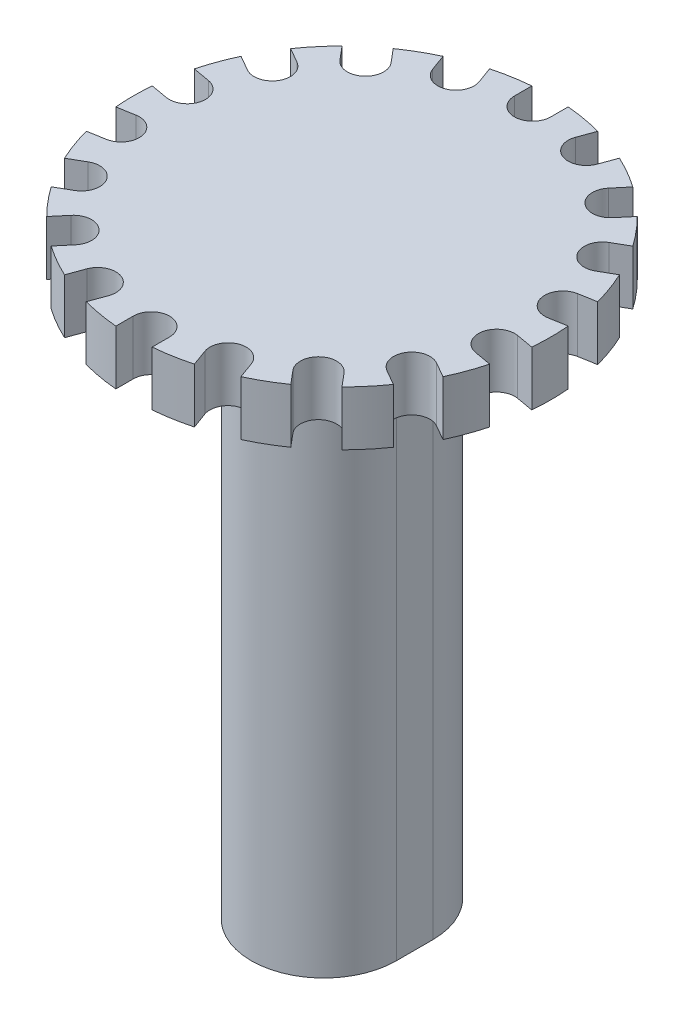
SolidWorks part; units mm, degrees
ref_plane "Front Plane" through (0, 0, 0) normal (0, 0, 1) x (1, 0, 0)
ref_plane "Top Plane" through (0, 0, 0) normal (0, 1, 0) x (1, 0, 0)
ref_plane "Right Plane" through (0, 0, 0) normal (1, 0, 0) x (0, 0, -1)
sketch "Sketch1" plane through (0, 0, 0) normal (0, 1, 0) x (1, 0, 0)
  line L0 (0, -0.8) -> (0, 0.8) construction
  line L1 (-2, -0.8) -> (-2, 0.8)
  line L2 (2, -0.8) -> (2, 0.8)
  line L3 (0, -1) -> (0, 1) construction
  line L4 (-4, -1) -> (-4, 1)
  line L5 (4, -1) -> (4, 1)
  arc A0 (-2, -0.8) -> (2, -0.8) centre (0, -0.8) ccw
  arc A1 (2, 0.8) -> (-2, 0.8) centre (0, 0.8) ccw
  arc A2 (-4, -1) -> (4, -1) centre (0, -1) ccw
  arc A3 (4, 1) -> (-4, 1) centre (0, 1) ccw
  point P2 (0, 0)
  point P9 (0, 0)
  dimension "D3" = 1.6
  dimension "D4" = 2
  dimension "D1" = 4
  dimension "D2" = 8
extrude "Boss-Extrude1" add sketch "Sketch1" along normal blind 30
sketch "Sketch2" plane through (0, 30, 0) normal (0, 1, 0) x (1, 0, 0)
  circle A0 centre (0, 0) radius 11.5
  dimension "D1" = 23
extrude "Boss-Extrude2" add sketch "Sketch2" along normal blind 3
sketch "Sketch3" plane through (0, 33, 0) normal (0, 1, 0) x (1, 0, 0)
  line L0 (0, 10.5) -> (0, 17.5) construction
  line L1 (-1, 10.5) -> (-1, 17.5)
  line L2 (1, 10.5) -> (1, 17.5)
  line L3 (3.5912, 9.8668) -> (5.9854, 16.4446) construction
  line L4 (2.6515, 10.2088) -> (5.0457, 16.7866)
  line L5 (4.5309, 9.5248) -> (6.925, 16.1026)
  line L6 (6.7493, 8.0435) -> (11.2488, 13.4058) construction
  line L7 (5.9832, 8.6863) -> (10.4827, 14.0486)
  line L8 (7.5153, 7.4007) -> (12.0148, 12.763)
  line L9 (9.0933, 5.25) -> (15.1554, 8.75) construction
  line L10 (8.5933, 6.116) -> (14.6554, 9.616)
  line L11 (9.5933, 4.384) -> (15.6554, 7.884)
  line L12 (10.3405, 1.8233) -> (17.2341, 3.0388) construction
  line L13 (10.1668, 2.8081) -> (17.0605, 4.0237)
  line L14 (10.5141, 0.8385) -> (17.4078, 2.054)
  line L15 (10.3405, -1.8233) -> (17.2341, -3.0388) construction
  line L16 (10.5141, -0.8385) -> (17.4078, -2.054)
  line L17 (10.1668, -2.8081) -> (17.0605, -4.0237)
  line L18 (9.0933, -5.25) -> (15.1554, -8.75) construction
  line L19 (9.5933, -4.384) -> (15.6554, -7.884)
  line L20 (8.5933, -6.116) -> (14.6554, -9.616)
  line L21 (6.7493, -8.0435) -> (11.2488, -13.4058) construction
  line L22 (7.5153, -7.4007) -> (12.0148, -12.763)
  line L23 (5.9832, -8.6863) -> (10.4827, -14.0486)
  line L24 (3.5912, -9.8668) -> (5.9854, -16.4446) construction
  line L25 (4.5309, -9.5248) -> (6.925, -16.1026)
  line L26 (2.6515, -10.2088) -> (5.0457, -16.7866)
  line L27 (0, -10.5) -> (0, -17.5) construction
  line L28 (1, -10.5) -> (1, -17.5)
  line L29 (-1, -10.5) -> (-1, -17.5)
  line L30 (-3.5912, -9.8668) -> (-5.9854, -16.4446) construction
  line L31 (-2.6515, -10.2088) -> (-5.0457, -16.7866)
  line L32 (-4.5309, -9.5248) -> (-6.925, -16.1026)
  line L33 (-6.7493, -8.0435) -> (-11.2488, -13.4058) construction
  line L34 (-5.9832, -8.6863) -> (-10.4827, -14.0486)
  line L35 (-7.5153, -7.4007) -> (-12.0148, -12.763)
  line L36 (-9.0933, -5.25) -> (-15.1554, -8.75) construction
  line L37 (-8.5933, -6.116) -> (-14.6554, -9.616)
  line L38 (-9.5933, -4.384) -> (-15.6554, -7.884)
  line L39 (-10.3405, -1.8233) -> (-17.2341, -3.0388) construction
  line L40 (-10.1668, -2.8081) -> (-17.0605, -4.0237)
  line L41 (-10.5141, -0.8385) -> (-17.4078, -2.054)
  line L42 (-10.3405, 1.8233) -> (-17.2341, 3.0388) construction
  line L43 (-10.5141, 0.8385) -> (-17.4078, 2.054)
  line L44 (-10.1668, 2.8081) -> (-17.0605, 4.0237)
  line L45 (-9.0933, 5.25) -> (-15.1554, 8.75) construction
  line L46 (-9.5933, 4.384) -> (-15.6554, 7.884)
  line L47 (-8.5933, 6.116) -> (-14.6554, 9.616)
  line L48 (-6.7493, 8.0435) -> (-11.2488, 13.4058) construction
  line L49 (-7.5153, 7.4007) -> (-12.0148, 12.763)
  line L50 (-5.9832, 8.6863) -> (-10.4827, 14.0486)
  line L51 (-3.5912, 9.8668) -> (-5.9854, 16.4446) construction
  line L52 (-4.5309, 9.5248) -> (-6.925, 16.1026)
  line L53 (-2.6515, 10.2088) -> (-5.0457, 16.7866)
  arc A0 (2.6515, 10.2088) -> (4.5309, 9.5248) centre (3.5912, 9.8668) ccw
  arc A1 (-1, 10.5) -> (1, 10.5) centre (0, 10.5) ccw
  arc A2 (1, 17.5) -> (-1, 17.5) centre (0, 17.5) ccw
  arc A3 (6.925, 16.1026) -> (5.0457, 16.7866) centre (5.9854, 16.4446) ccw
  arc A4 (5.9832, 8.6863) -> (7.5153, 7.4007) centre (6.7493, 8.0435) ccw
  arc A5 (12.0148, 12.763) -> (10.4827, 14.0486) centre (11.2488, 13.4058) ccw
  arc A6 (8.5933, 6.116) -> (9.5933, 4.384) centre (9.0933, 5.25) ccw
  arc A7 (15.6554, 7.884) -> (14.6554, 9.616) centre (15.1554, 8.75) ccw
  arc A8 (10.1668, 2.8081) -> (10.5141, 0.8385) centre (10.3405, 1.8233) ccw
  arc A9 (17.4078, 2.054) -> (17.0605, 4.0237) centre (17.2341, 3.0388) ccw
  arc A10 (10.5141, -0.8385) -> (10.1668, -2.8081) centre (10.3405, -1.8233) ccw
  arc A11 (17.0605, -4.0237) -> (17.4078, -2.054) centre (17.2341, -3.0388) ccw
  arc A12 (9.5933, -4.384) -> (8.5933, -6.116) centre (9.0933, -5.25) ccw
  arc A13 (14.6554, -9.616) -> (15.6554, -7.884) centre (15.1554, -8.75) ccw
  arc A14 (7.5153, -7.4007) -> (5.9832, -8.6863) centre (6.7493, -8.0435) ccw
  arc A15 (10.4827, -14.0486) -> (12.0148, -12.763) centre (11.2488, -13.4058) ccw
  arc A16 (4.5309, -9.5248) -> (2.6515, -10.2088) centre (3.5912, -9.8668) ccw
  arc A17 (5.0457, -16.7866) -> (6.925, -16.1026) centre (5.9854, -16.4446) ccw
  arc A18 (1, -10.5) -> (-1, -10.5) centre (0, -10.5) ccw
  arc A19 (-1, -17.5) -> (1, -17.5) centre (0, -17.5) ccw
  arc A20 (-2.6515, -10.2088) -> (-4.5309, -9.5248) centre (-3.5912, -9.8668) ccw
  arc A21 (-6.925, -16.1026) -> (-5.0457, -16.7866) centre (-5.9854, -16.4446) ccw
  arc A22 (-5.9832, -8.6863) -> (-7.5153, -7.4007) centre (-6.7493, -8.0435) ccw
  arc A23 (-12.0148, -12.763) -> (-10.4827, -14.0486) centre (-11.2488, -13.4058) ccw
  arc A24 (-8.5933, -6.116) -> (-9.5933, -4.384) centre (-9.0933, -5.25) ccw
  arc A25 (-15.6554, -7.884) -> (-14.6554, -9.616) centre (-15.1554, -8.75) ccw
  arc A26 (-10.1668, -2.8081) -> (-10.5141, -0.8385) centre (-10.3405, -1.8233) ccw
  arc A27 (-17.4078, -2.054) -> (-17.0605, -4.0237) centre (-17.2341, -3.0388) ccw
  arc A28 (-10.5141, 0.8385) -> (-10.1668, 2.8081) centre (-10.3405, 1.8233) ccw
  arc A29 (-17.0605, 4.0237) -> (-17.4078, 2.054) centre (-17.2341, 3.0388) ccw
  arc A30 (-9.5933, 4.384) -> (-8.5933, 6.116) centre (-9.0933, 5.25) ccw
  arc A31 (-14.6554, 9.616) -> (-15.6554, 7.884) centre (-15.1554, 8.75) ccw
  arc A32 (-7.5153, 7.4007) -> (-5.9832, 8.6863) centre (-6.7493, 8.0435) ccw
  arc A33 (-10.4827, 14.0486) -> (-12.0148, 12.763) centre (-11.2488, 13.4058) ccw
  arc A34 (-4.5309, 9.5248) -> (-2.6515, 10.2088) centre (-3.5912, 9.8668) ccw
  arc A35 (-5.0457, 16.7866) -> (-6.925, 16.1026) centre (-5.9854, 16.4446) ccw
  point P2 (0, 14)
  point P11 (4.7883, 13.1557)
  point P18 (8.999, 10.7246)
  point P25 (12.1244, 7)
  point P32 (13.7873, 2.4311)
  point P39 (13.7873, -2.4311)
  point P46 (12.1244, -7)
  point P53 (8.999, -10.7246)
  point P60 (4.7883, -13.1557)
  point P67 (0, -14)
  point P74 (-4.7883, -13.1557)
  point P81 (-8.999, -10.7246)
  point P88 (-12.1244, -7)
  point P95 (-13.7873, -2.4311)
  point P102 (-13.7873, 2.4311)
  point P109 (-12.1244, 7)
  point P114 (0, 0)
  point P117 (-8.999, 10.7246)
  point P124 (-4.7883, 13.1557)
  dimension "D1" = 2
  dimension "D3" = 7
  dimension "D2" = 14
extrude "Cut-Extrude1" cut sketch "Sketch3" against normal through all
